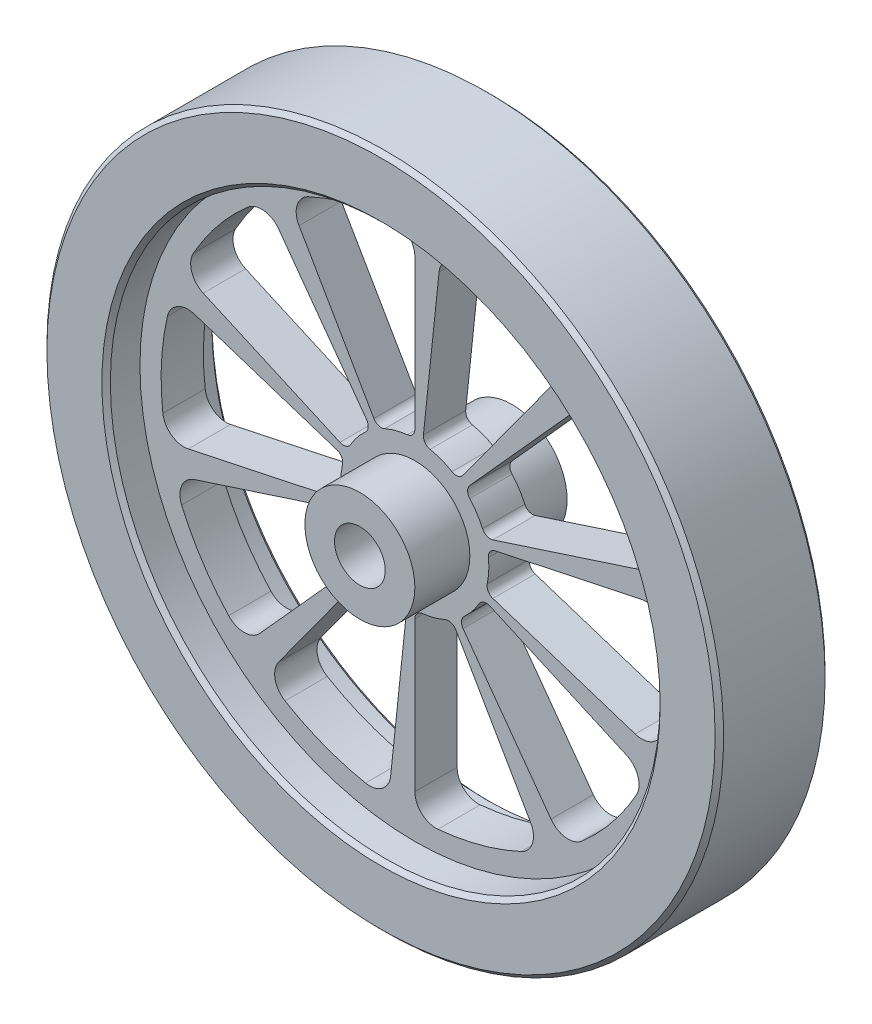
SolidWorks part; units mm, degrees
ref_plane "Front Plane" through (0, 0, 0) normal (0, 0, 1) x (1, 0, 0)
ref_plane "Top Plane" through (0, 0, 0) normal (0, 1, 0) x (1, 0, 0)
ref_plane "Right Plane" through (0, 0, 0) normal (1, 0, 0) x (0, 0, -1)
sketch "Sketch1" plane through (0, 0, 0) normal (0, 0, 1) x (1, 0, 0)
  circle A0 centre (0, 0) radius 80
  circle A1 centre (0, 0) radius 6
extrude "Boss-Extrude1" add sketch "Sketch1" along normal mid plane 26
sketch "Sketch2" plane through (0, 0, 13) normal (0, 0, 1) x (1, 0, 0)
  circle A0 centre (0, 0) radius 65
extrude "Cut-Extrude1" cut sketch "Sketch2" against normal blind 8
mirror "Mirror1" about plane through (0, 0, 0) normal (0, 0, 1) of "Cut-Extrude1"
sketch "Sketch3" plane through (0, 0, 0) normal (0, 0, 1) x (1, 0, 0)
  circle A0 centre (0, 0) radius 13
extrude "Boss-Extrude2" add sketch "Sketch3" along normal mid plane 36
chamfer "Chamfer1" distance 1 angle 45 1 edges at (80, 0, -13)
sketch "Sketch4" plane through (0, 0, 18) normal (0, 0, 1) x (1, 0, 0)
  circle A0 centre (0, 0) radius 6
extrude "Cut-Extrude2" cut sketch "Sketch4" against normal through all
sketch "Sketch5" plane through (0, 0, 5) normal (0, 0, 1) x (1, 0, 0)
  line L0 (0, 17.5) -> (0, 60) construction
  line L1 (0, 0) -> (-30, 51.9615) construction
  line L2 (0, 54.7723) -> (0, 19.3972)
  line L3 (-9.6986, 16.7984) -> (-27.3861, 47.4342)
  arc A0 (-5.4545, 59.7516) -> (-25.152, 54.4736) centre (0, 0) ccw
  arc A1 (-1.7949, 17.4077) -> (-7.1495, 15.973) centre (0, 0) ccw
  arc A2 (-5.4545, 59.7516) -> (0, 54.7723) centre (-5, 54.7723) cw
  arc A3 (-25.152, 54.4736) -> (-27.3861, 47.4342) centre (-23.056, 49.9342) ccw
  arc A4 (0, 19.3972) -> (-1.7949, 17.4077) centre (-2, 19.3972) cw
  arc A5 (-7.1495, 15.973) -> (-9.6986, 16.7984) centre (-7.9665, 17.7984) cw
  point P17 (-8.75, 15.1554)
  dimension "D1" = 30
  dimension "D2" = 5
  dimension "D3" = 2
extrude "Cut-Extrude3" cut sketch "Sketch5" against normal through all
pattern_circular "CirPattern1" count 10 over 360 about axis through (0, 0, 0) along (0, 0, 1) of "Cut-Extrude3"
